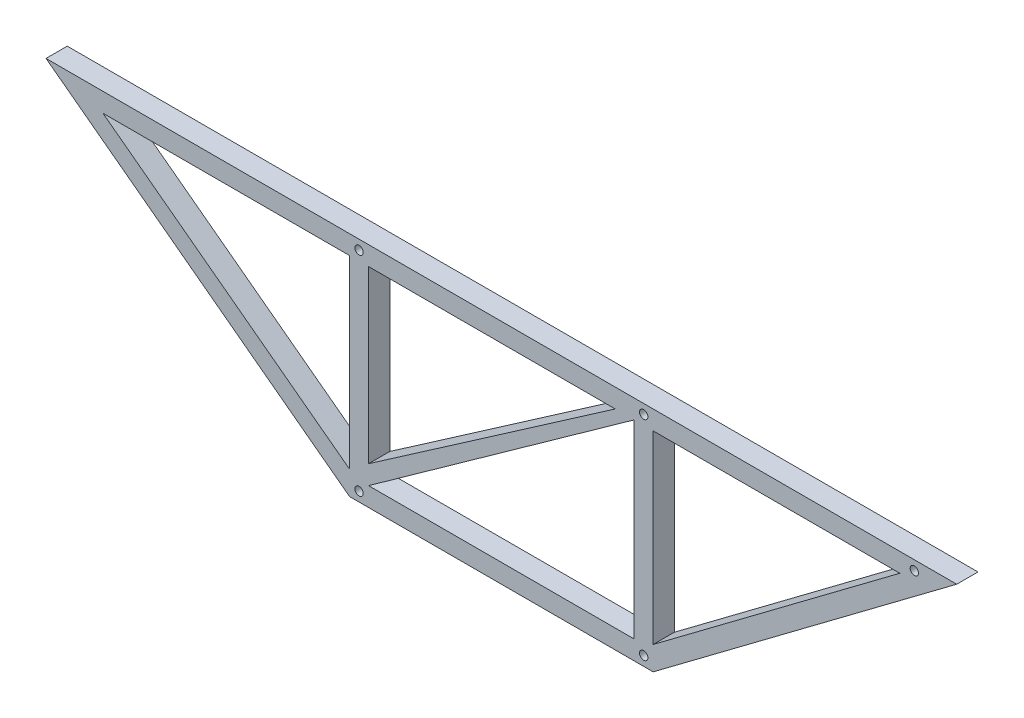
SolidWorks part; units mm, degrees
material "AISI 1020"
ref_plane "Front Plane" through (0, 0, 0) normal (0, 0, 1) x (1, 0, 0)
ref_plane "Top Plane" through (0, 0, 0) normal (0, 1, 0) x (1, 0, 0)
ref_plane "Right Plane" through (0, 0, 0) normal (1, 0, 0) x (0, 0, -1)
sketch "Sketch1" plane through (0, 0, 0) normal (0, 0, 1) x (1, 0, 0)
  line L0 (-600, 0) -> (600, 0)
  line L1 (-600, 0) -> (-200, -300)
  line L2 (-200, -300) -> (200, -300)
  line L3 (200, -300) -> (600, 0)
  point P4 (0, 0)
  dimension "D1" = 1200
  dimension "D2" = 300
  dimension "D3" = 400
  dimension "D4" = 400
extrude "Boss-Extrude1" add sketch "Sketch1" along normal mid plane 28
sketch "Sketch2" plane through (0, 0, 14) normal (0, 0, 1) x (1, 0, 0)
  line L0 (-175, -275) -> (175, -275)
  line L1 (175, -275) -> (175, -25)
  line L2 (175, -25) -> (-175, -275)
  line L3 (-200, -300) -> (200, -300) construction
  line L4 (600, 0) -> (-600, 0) construction
  line L5 (-175, -25) -> (-175, -250)
  line L6 (-175, -25) -> (150, -25)
  line L7 (150, -25) -> (-175, -250)
  dimension "D1" = 25
  dimension "D2" = 25
  dimension "D3" = 25
  dimension "D4" = 25
  dimension "D5" = 25
  dimension "D6" = 25
extrude "Cut-Extrude1" cut sketch "Sketch2" against normal blind 28
sketch "Sketch3" plane through (0, 0, 14) normal (0, 0, 1) x (1, 0, 0)
  line L0 (-525, -25) -> (-200, -25)
  line L1 (-200, -25) -> (-200, -268.75)
  line L2 (-200, -268.75) -> (-525, -25)
  line L3 (600, 0) -> (-600, 0) construction
  line L4 (-600, 0) -> (-200, -300) construction
  line L5 (-175, -25) -> (-175, -250) construction
  dimension "D1" = 25
  dimension "D2" = 25
  dimension "D3" = 25
  dimension "D4" = 25
extrude "Cut-Extrude2" cut sketch "Sketch3" against normal blind 28
sketch "Sketch4" plane through (0, 0, 14) normal (0, 0, 1) x (1, 0, 0)
  line L0 (200, -25) -> (525, -25)
  line L1 (525, -25) -> (200, -268.75)
  line L2 (200, -268.75) -> (200, -25)
  line L3 (200, -300) -> (600, 0) construction
  line L4 (600, 0) -> (-600, 0) construction
  dimension "D1" = 25
  dimension "D2" = 25
  dimension "D3" = 25
  dimension "D4" = 25
extrude "Cut-Extrude3" cut sketch "Sketch4" against normal blind 28
sketch "Sketch5" plane through (0, 0, 14) normal (0, 0, 1) x (1, 0, 0)
  line L0 (600, 0) -> (-600, 0) construction
  line L1 (-200, -268.75) -> (-200, -25) construction
  line L2 (200, -25) -> (200, -268.75) construction
  line L4 (-200, -300) -> (200, -300) construction
  line L5 (175, -275) -> (175, -25) construction
  circle A0 centre (-187.5, -12.5) radius 5.5
  circle A1 centre (-187.5, -287.5) radius 5.5
  circle A2 centre (187.5, -287.5) radius 5.5
  circle A3 centre (187.5, -12.5) radius 5.5
  circle A4 centre (544.1101, -12.5) radius 5.5
  dimension "D1" = 11
  dimension "D2" = 11
  dimension "D3" = 11
  dimension "D4" = 11
  dimension "D5" = 11
  dimension "D6" = 12.5
  dimension "D7" = 12.5
  dimension "D8" = 12.5
  dimension "D9" = 12.5
  dimension "D10" = 12.5
  dimension "D11" = 12.5
  dimension "D12" = 12.5
  dimension "D13" = 12.5
  dimension "D14" = 12.5
extrude "Cut-Extrude4" cut sketch "Sketch5" against normal blind 28
